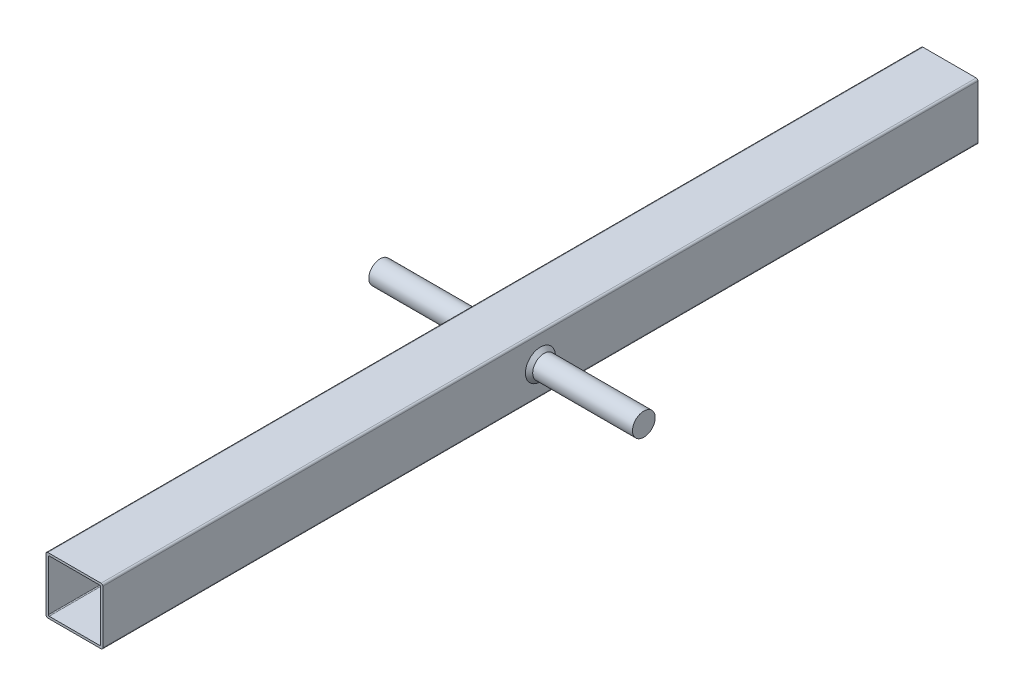
SolidWorks part; units mm, degrees
ref_plane "Front Plane" through (0, 0, 0) normal (0, 0, 1) x (1, 0, 0)
ref_plane "Top Plane" through (0, 0, 0) normal (0, 1, 0) x (1, 0, 0)
ref_plane "Right Plane" through (0, 0, 0) normal (1, 0, 0) x (0, 0, -1)
sketch "Sketch1" plane through (0, 0, 0) normal (0, 0, 1) x (1, 0, 0)
  line L1 (19.8438, -19.8437) -> (-19.8438, -19.8438)
  line L2 (19.8438, -19.8437) -> (19.8438, 19.8438)
  line L3 (19.8438, 19.8438) -> (-19.8438, 19.8438)
  line L4 (-19.8438, -19.8438) -> (-19.8438, 19.8438)
  line L5 (19.8438, -19.8437) -> (-19.8438, 19.8438) construction
  line L6 (19.8438, 19.8438) -> (-19.8438, -19.8438) construction
  line L7 (-18.2563, 18.2563) -> (18.2562, 18.2563)
  line L8 (-18.2563, 18.2563) -> (-18.2562, -18.2562)
  line L9 (-18.2562, -18.2562) -> (18.2563, -18.2562)
  line L10 (18.2562, 18.2563) -> (18.2563, -18.2562)
  line L11 (-18.2563, 18.2563) -> (18.2563, -18.2562) construction
  line L12 (-18.2562, -18.2562) -> (18.2562, 18.2563) construction
  point P0 (0, 0)
  point P6 (0, 0)
  dimension "D1" = 39.6875
  dimension "D2" = 36.5125
extrude "Boss-Extrude1" add sketch "Sketch1" along normal mid plane 611.1875
fillet "Fillet1" radius 1.27 4 edges at (19.8438, -19.8437, 0) (-19.8438, -19.8438, 0) (-19.8438, 19.8438, 0) (19.8438, 19.8438, 0)
fillet "Fillet2" radius 0.635 4 edges at (18.2563, -18.2562, 0) (18.2562, 18.2563, 0) (-18.2562, -18.2562, 0) (-18.2563, 18.2563, 0)
sketch "Sketch2" plane through (0, 0, 0) normal (1, 0, 0) x (0, 0, -1)
  circle A0 centre (0, 0) radius 7.9375
  dimension "D1" = 15.875
extrude "Boss-Extrude2" add sketch "Sketch2" along normal mid plane 184.15
chamfer "Chamfer1" distance 2.54 angle 45 2 edges at (19.8438, 0, 7.9375) (-19.8438, 0, -7.9375)
